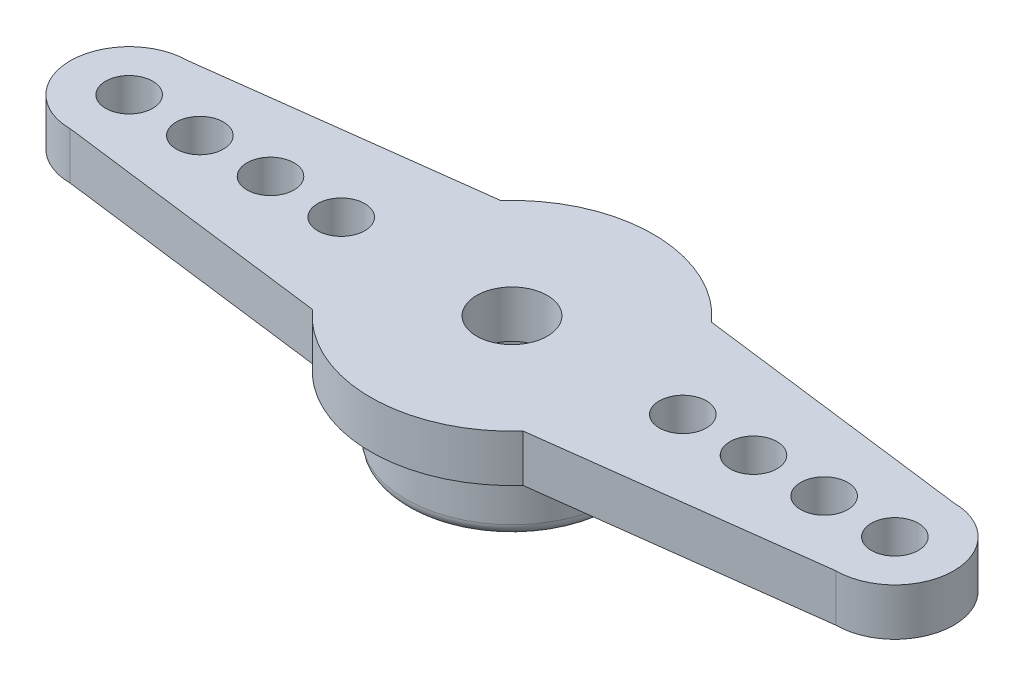
SolidWorks part; units mm, degrees
ref_plane "Front Plane" through (0, 0, 0) normal (0, 0, 1) x (1, 0, 0)
ref_plane "Top Plane" through (0, 0, 0) normal (0, 1, 0) x (1, 0, 0)
ref_plane "Right Plane" through (0, 0, 0) normal (1, 0, 0) x (0, 0, -1)
sketch "Sketch1" plane through (0, 0, 0) normal (0, 1, 0) x (1, 0, 0)
  line L1 (4.4721, 4) -> (16.25, 2.5)
  line L2 (4.4721, -4) -> (16.25, -2.5)
  line L3 (-16.25, 2.5) -> (-4.4721, 4)
  line L4 (-16.25, -2.5) -> (-4.4721, -4)
  arc A0 (-16.25, 2.5) -> (-16.25, -2.5) centre (-16.25, 0) ccw
  arc A1 (16.25, -2.5) -> (16.25, 2.5) centre (16.25, 0) ccw
  arc A2 (-4.4721, -4) -> (4.4721, -4) centre (0, 0) ccw
  arc A3 (4.4721, 4) -> (-4.4721, 4) centre (0, 0) ccw
  point P1 (0, 0)
  point P14 (0, 0)
  dimension "D1" = 5
  dimension "D2" = 5
  dimension "D4" = 12
  dimension "D3" = 16.25
  dimension "D5" = 16.25
  dimension "D6" = 8
extrude "Boss-Extrude1" add sketch "Sketch1" along normal blind 2
sketch "Sketch3" plane through (0, 2, 0) normal (0, 1, 0) x (1, 0, 0)
  line L0 (0, 6) -> (0, -6) construction
  line L1 (-3.8663, 0) -> (3.314, 0) construction
  circle A0 centre (-16.25, 0) radius 1
  arc A1 (4.4721, 4) -> (-4.4721, 4) centre (0, 0) ccw construction
  arc A2 (-4.4721, -4) -> (4.4721, -4) centre (0, 0) ccw construction
  arc A3 (-16.25, 2.5) -> (-16.25, -2.5) centre (-16.25, 0) ccw construction
  circle A4 centre (-13.25, 0) radius 1
  circle A5 centre (-10.25, 0) radius 1
  circle A6 centre (-7.25, 0) radius 1
  circle A7 centre (7.25, 0) radius 1
  circle A8 centre (10.25, 0) radius 1
  circle A9 centre (13.25, 0) radius 1
  circle A10 centre (16.25, 0) radius 1
  circle A11 centre (0, 0) radius 1.5
  dimension "D1" = 2
  dimension "D3" = 3
  dimension "D2" = 4
extrude "Cut-Extrude1" cut sketch "Sketch3" against normal through all contours A5 | A6 | A11 | A9 | A10 | A8 | A0 | A4 | A7
sketch "Sketch4" plane through (0, 0, 0) normal (0, -1, 0) x (1, 0, 0)
  circle A0 centre (0, 0) radius 3.1796
  circle A1 centre (0, 0) radius 4.5
  dimension "D1" = 9
extrude "Boss-Extrude2" add sketch "Sketch4" along normal blind 3 contours A1 A0
fillet "Fillet1" radius 0.5 1 edges at (0, -3, -4.5)
